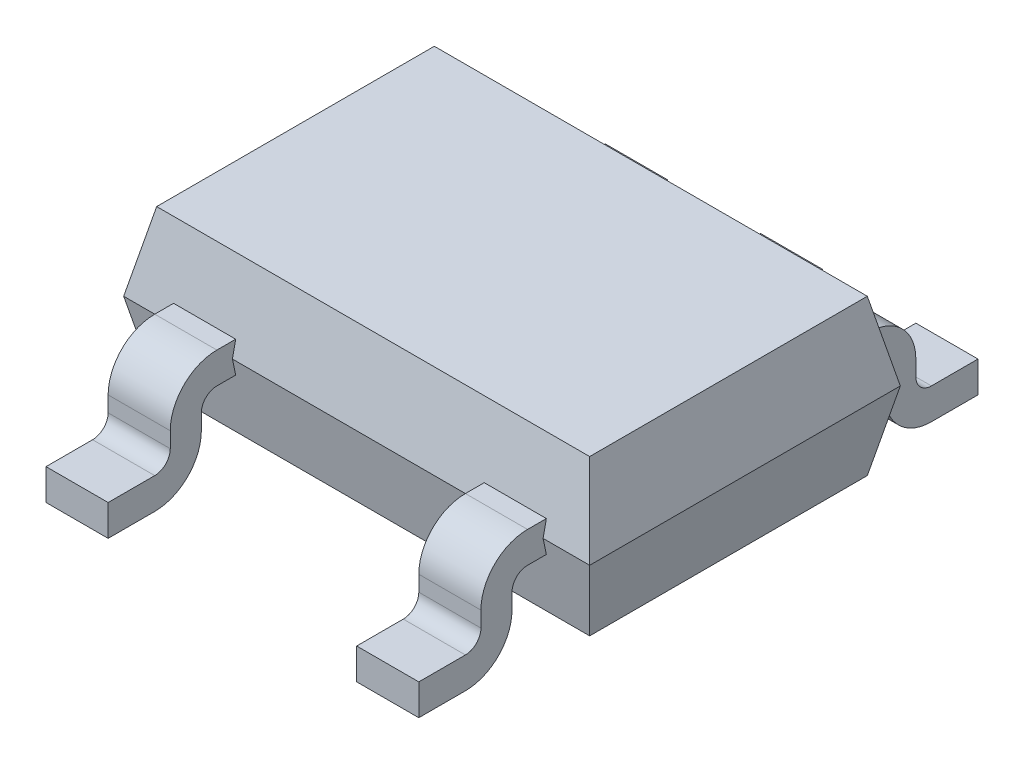
SolidWorks part; units mm, degrees
ref_plane "Front Plane" through (0, 0, 0) normal (0, 0, 1) x (1, 0, 0)
ref_plane "Top Plane" through (0, 0, 0) normal (0, 1, 0) x (1, 0, 0)
ref_plane "Right Plane" through (0, 0, 0) normal (1, 0, 0) x (0, 0, -1)
sketch "BaseS" plane through (0, 0, 0) normal (0, 1, 0) x (1, 0, 0)
  line L1 (-1.5, 1) -> (1.5, 1)
  line L2 (-1.5, 1) -> (-1.5, -1)
  line L3 (-1.5, -1) -> (1.5, -1)
  line L4 (1.5, 1) -> (1.5, -1)
  line L5 (-1.5, 1) -> (1.5, -1) construction
  line L6 (-1.5, -1) -> (1.5, 1) construction
  point P0 (0, 0)
  dimension "Width" = 3
  dimension "Length" = 2
extrude "Base" add sketch "BaseS" along normal mid plane 1 draft 12
sketch "VInSolderJointS" plane through (0, 0, 0) normal (1, 0, 0) x (0, 0, -1)
  line L0 (0.9, 0) -> (1.1, 0)
  line L1 (1.3, -0.2) -> (1.3, -0.3)
  line L2 (1.5, -0.5) -> (1.8, -0.5)
  line L3 (-0.8937, -0.5) -> (0.8937, -0.5) construction
  line L4 (0, -0.5) -> (0, 0) construction
  line L5 (-0.8937, -0.5) -> (0.8937, -0.5) construction
  line L6 (-1.5, -0.5) -> (-1.8, -0.5) construction
  line L7 (-1.3, -0.2) -> (-1.3, -0.3) construction
  line L8 (-0.9, 0) -> (-1.1, 0) construction
  arc A0 (1.1, 0) -> (1.3, -0.2) centre (1.1, -0.2) cw
  arc A1 (1.5, -0.5) -> (1.3, -0.3) centre (1.5, -0.3) cw
  arc A2 (-1.5, -0.5) -> (-1.3, -0.3) centre (-1.5, -0.3) ccw construction
  arc A3 (-1.1, 0) -> (-1.3, -0.2) centre (-1.1, -0.2) ccw construction
  dimension "Radius" = 0.2
  dimension "InnerLength" = 0.1
  dimension "TopOuterLength" = 0.1
  dimension "BottomLength" = 0.3
extrude "VInSolderJoint" add sketch "VInSolderJointS" along normal mid plane 0.4 thin thin type mid plane wall 0.2
pattern_linear "SJLP" count 2 spacing 1 along (1, 0, 0) count 2 spacing 1 along (-1, 0, 0) of "VInSolderJoint"
ref_plane "Plane1" through (1, 0, 0) normal (1, 0, 0) x (0, 0, -1)
sketch "VOutSolderJointS" plane through (1, 0, 0) normal (1, 0, 0) x (0, 0, -1)
  line L0 (-1.5, -0.5) -> (-1.8, -0.5) construction
  line L1 (-1.3, -0.2) -> (-1.3, -0.3) construction
  line L2 (-0.9, 0) -> (-1.1, 0) construction
  line L3 (-1.5, -0.5) -> (-1.8, -0.5)
  line L4 (-1.3, -0.2) -> (-1.3, -0.3)
  line L5 (-0.9, 0) -> (-1.1, 0)
  arc A0 (-1.5, -0.5) -> (-1.3, -0.3) centre (-1.5, -0.3) ccw construction
  arc A1 (-1.1, 0) -> (-1.3, -0.2) centre (-1.1, -0.2) ccw construction
  arc A2 (-1.5, -0.5) -> (-1.3, -0.3) centre (-1.5, -0.3) ccw
  arc A3 (-1.1, 0) -> (-1.3, -0.2) centre (-1.1, -0.2) ccw
extrude "VOutSolderJoint" add sketch "VOutSolderJointS" along normal mid plane 0.4 thin thin type mid plane wall 0.2
mirror "VOSJ HM" about plane through (0, 0, 0) normal (1, 0, 0) of "VOutSolderJoint"
equation "\"Width@VOutSolderJoint\"=\"Width@VInSolderJoint\""
equation "\"Height@VOutSolderJoint\"=\"Height@VInSolderJoint\""
